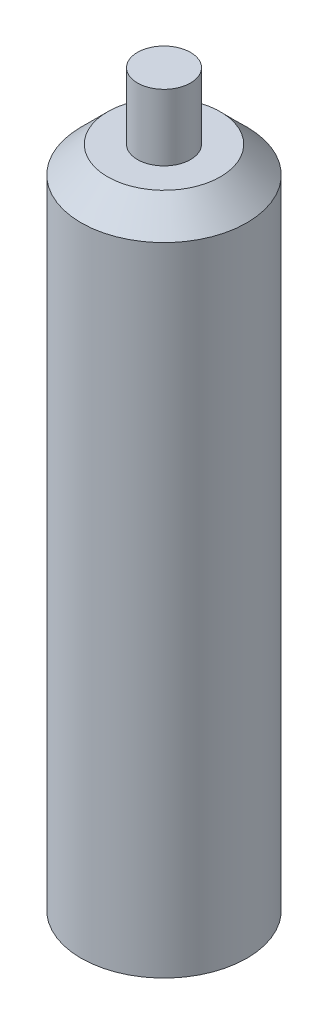
SolidWorks part; units mm, degrees
ref_plane "Front Plane" through (0, 0, 0) normal (0, 0, 1) x (1, 0, 0)
ref_plane "Top Plane" through (0, 0, 0) normal (0, 1, 0) x (1, 0, 0)
ref_plane "Right Plane" through (0, 0, 0) normal (1, 0, 0) x (0, 0, -1)
sketch "Sketch1" plane through (0, 0, 0) normal (0, 1, 0) x (1, 0, 0)
  circle A0 centre (0, 0) radius 6.25
extrude "Boss-Extrude1" add sketch "Sketch1" along normal blind 50
sketch "Sketch2" plane through (0, 50, 0) normal (0, 1, 0) x (1, 0, 0)
  circle A0 centre (0, 0) radius 2
extrude "Boss-Extrude2" add sketch "Sketch2" along normal blind 5
chamfer "Chamfer1" distance 2 angle 45 1 edges at (0, 50, 6.25)
